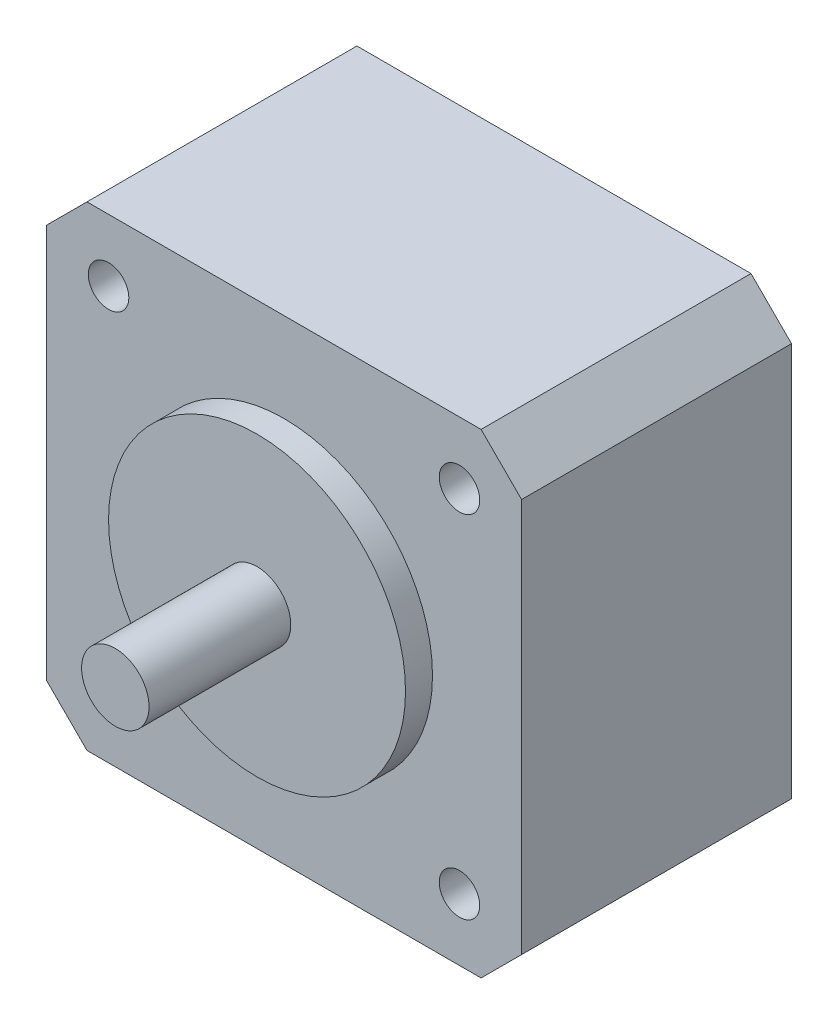
SolidWorks part; units mm, degrees
material "1060 Alloy"
ref_plane "Front Plane" through (0, 0, 0) normal (0, 0, 1) x (1, 0, 0)
ref_plane "Top Plane" through (0, 0, 0) normal (0, 1, 0) x (1, 0, 0)
ref_plane "Right Plane" through (0, 0, 0) normal (1, 0, 0) x (0, 0, -1)
sketch "Sketch1" plane through (0, 0, 0) normal (0, 0, 1) x (1, 0, 0)
  line L1 (-17.6, 17.6) -> (17.6, 17.6)
  line L2 (-17.6, 17.6) -> (-17.6, -17.6)
  line L3 (-17.6, -17.6) -> (17.6, -17.6)
  line L4 (17.6, 17.6) -> (17.6, -17.6)
  line L5 (-17.6, 17.6) -> (17.6, -17.6) construction
  line L6 (-17.6, -17.6) -> (17.6, 17.6) construction
  point P0 (0, 0)
  dimension "D1" = 35.2
  dimension "D2" = 35.2
extrude "Boss-Extrude1" add sketch "Sketch1" along normal blind 20
sketch "Sketch2" plane through (0, 0, 20) normal (0, 0, 1) x (1, 0, 0)
  circle A0 centre (0, 0) radius 11
  dimension "D1" = 22
extrude "Boss-Extrude2" add sketch "Sketch2" along normal blind 2
sketch "Sketch3" plane through (0, 0, 22) normal (0, 0, 1) x (1, 0, 0)
  circle A0 centre (0, 0) radius 2.5
  dimension "D1" = 5
extrude "Boss-Extrude3" add sketch "Sketch3" along normal blind 10.5
sketch "Sketch4" plane through (0, 0, 20) normal (0, 0, 1) x (1, 0, 0)
  line L0 (-13, 13) -> (13, -13) construction
  circle A0 centre (13, 13) radius 1.5
  circle A1 centre (13, -13) radius 1.5
  circle A2 centre (-13, -13) radius 1.5
  circle A3 centre (-13, 13) radius 1.5
  point P8 (0, 0)
  point P9 (0, 0)
  point P10 (0, 0)
  point P11 (13.7757, 11.9016)
  dimension "D3" = 3
  dimension "D4" = 3
  dimension "D5" = 3
  dimension "D6" = 3
  dimension "D1" = 26
  dimension "D2" = 26
extrude "Cut-Extrude1" cut sketch "Sketch4" against normal blind 4.5
chamfer "Chamfer1" distance 3 angle 45 4 edges at (-17.6, -17.6, 10) (-17.6, 17.6, 10) (17.6, -17.6, 10) (17.6, 17.6, 10)
